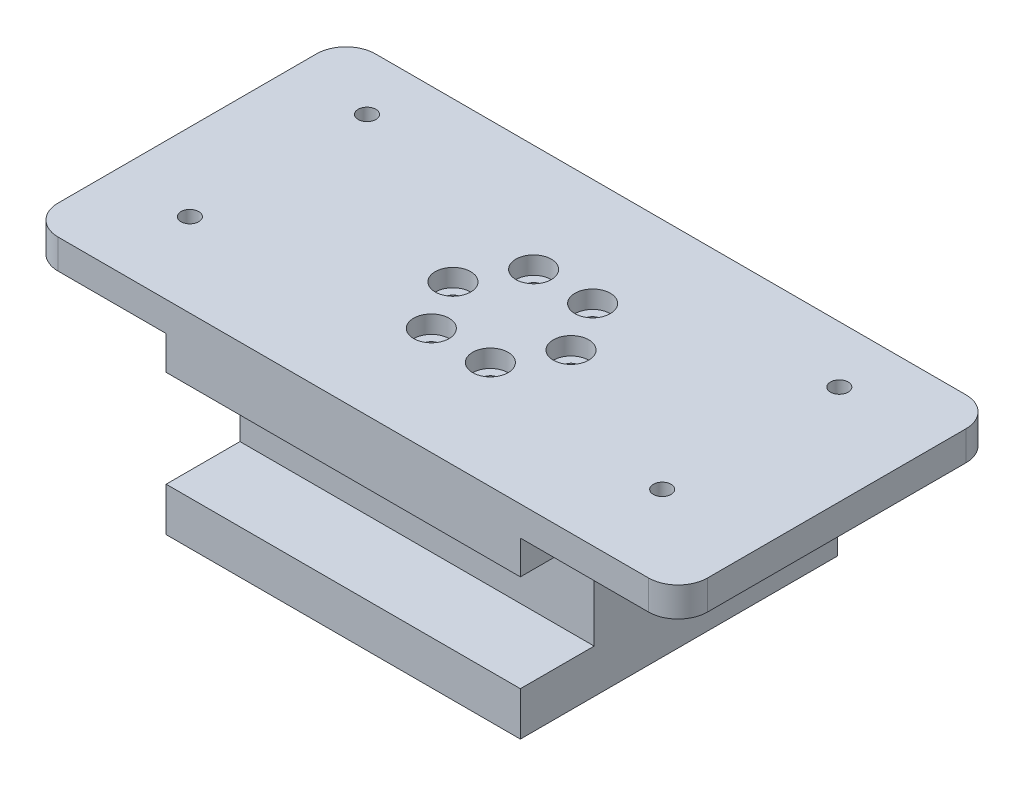
SolidWorks part; units mm, degrees
ref_plane "Front Plane" through (0, 0, 0) normal (0, 0, 1) x (1, 0, 0)
ref_plane "Top Plane" through (0, 0, 0) normal (0, 1, 0) x (1, 0, 0)
ref_plane "Right Plane" through (0, 0, 0) normal (1, 0, 0) x (0, 0, -1)
sketch "Sketch1" plane through (0, 0, 0) normal (0, 1, 0) x (1, 0, 0)
  line L1 (0, 0) -> (60, 0)
  line L2 (0, 0) -> (0, 53.75)
  line L3 (0, 53.75) -> (60, 53.75)
  line L4 (60, 0) -> (60, 53.75)
  dimension "D1" = 53.75
  dimension "D2" = 60
extrude "Boss-Extrude1" add sketch "Sketch1" along normal blind 29.5
sketch "Sketch2" plane through (0, 29.5, 0) normal (0, 1, 0) x (1, 0, 0)
  line L0 (60, 53.75) -> (0, 53.75) construction
  line L1 (-23.293, 0) -> (86.707, 0)
  line L2 (-23.293, 0) -> (-23.293, 53.75)
  line L3 (-23.293, 53.75) -> (86.707, 53.75)
  line L4 (86.707, 0) -> (86.707, 53.75)
  dimension "D1" = 110
  dimension "D2" = 53.75
extrude "Boss-Extrude3" add sketch "Sketch2" along normal blind 5
sketch "Sketch3" plane through (0, 0, 0) normal (-1, 0, 0) x (0, 0, 1)
  line L0 (0, 29.5) -> (0, 0) construction
  line L1 (0, 23.8) -> (-12.5, 23.8)
  line L2 (0, 23.8) -> (0, 7.4)
  line L3 (0, 7.4) -> (-12.5, 7.4)
  line L4 (-12.5, 23.8) -> (-12.5, 7.4)
  line L5 (-53.75, 0) -> (0, 0) construction
  dimension "D1" = 7.4
  dimension "D2" = 16.4
  dimension "D3" = 12.5
extrude "Cut-Extrude1" cut sketch "Sketch3" against normal through all
sketch "Sketch4" plane through (0, 34.5, 0) normal (0, 1, 0) x (1, 0, 0)
  line L0 (-23.293, 0) -> (86.707, 0) construction
  line L2 (-23.293, 53.75) -> (-23.293, 0) construction
  circle A0 centre (-10.133, 14.155) radius 1.5
  circle A2 centre (69.867, 14.155) radius 1.5
  circle A3 centre (-10.133, 44.155) radius 1.5
  circle A5 centre (69.867, 44.155) radius 1.5
  circle A7 centre (29.867, 14.155) radius 1.5 [skipped]
  dimension "D1" = 3
  dimension "D2" = 3
  dimension "D4" = 14.155
  dimension "D5" = 13.16
  dimension "D3" = 2
extrude "Cut-Extrude2" cut sketch "Sketch4" against normal through all
sketch "Sketch7" plane through (0, 34.5, 0) normal (0, 1, 0) x (1, 0, 0)
  line L0 (-23.293, 26.875) -> (31.707, 26.875) construction
  line L1 (-23.293, 53.75) -> (-23.293, 0) construction
  circle A0 centre (41.707, 26.875) radius 3
  circle A1 centre (36.707, 18.2147) radius 3
  circle A2 centre (26.707, 18.2147) radius 3
  circle A3 centre (21.707, 26.875) radius 3
  circle A4 centre (26.707, 35.5353) radius 3
  circle A5 centre (36.707, 35.5353) radius 3
  point P19 (31.707, 26.875)
  dimension "D3" = 6
  dimension "D1" = 55
  dimension "D2" = 10
  dimension "D4" = 6
extrude "Cut-Extrude3" cut sketch "Sketch7" against normal blind 3
sketch "Sketch8" plane through (0, 34.5, 0) normal (0, 1, 0) x (1, 0, 0)
  line L0 (-23.293, 26.875) -> (31.707, 26.875) construction
  line L1 (-23.293, 53.75) -> (-23.293, 0) construction
  circle A0 centre (41.707, 26.875) radius 1.5
  circle A6 centre (36.707, 18.2147) radius 1.5
  circle A7 centre (26.707, 18.2147) radius 1.5
  circle A8 centre (21.707, 26.875) radius 1.5
  circle A9 centre (26.707, 35.5353) radius 1.5
  circle A10 centre (36.707, 35.5353) radius 1.5
  point P19 (29.207, 22.5449)
  point P21 (31.707, 26.875)
  dimension "D2" = 3
  dimension "D1" = 55
  dimension "D3" = 10
  dimension "D4" = 6
extrude "Cut-Extrude4" cut sketch "Sketch8" against normal through all
fillet "Fillet1" radius 5 4 edges at (-23.293, 32, -53.75) (86.707, 32, -53.75) (86.707, 32, 0) (-23.293, 32, 0)
sketch "Sketch9" plane through (0, 34.5, 0) normal (0, 1, 0) x (1, 0, 0)
  line L0 (-23.293, 26.875) -> (31.707, 26.875) construction
  line L1 (-23.293, 48.75) -> (-23.293, 5) construction
  dimension "D1" = 55
